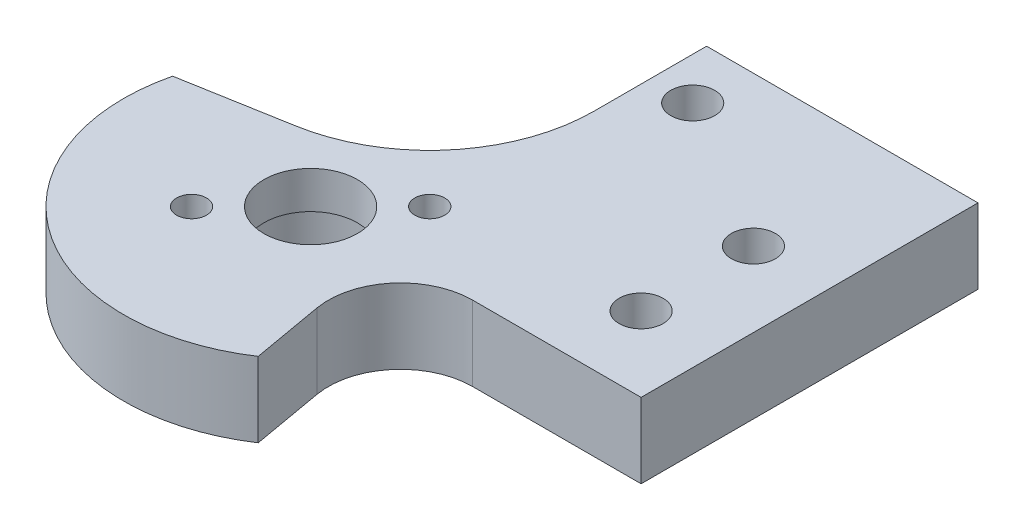
SolidWorks part; units mm, degrees
ref_plane "前视基准面" through (0, 0, 0) normal (0, 0, 1) x (1, 0, 0)
ref_plane "上视基准面" through (0, 0, 0) normal (0, 1, 0) x (1, 0, 0)
ref_plane "右视基准面" through (0, 0, 0) normal (1, 0, 0) x (0, 0, -1)
sketch "草图3" plane through (0, 0, 0) normal (0, 1, 0) x (1, 0, 0)
  line L1 (0, 0) -> (14.5, 0)
  line L2 (0, 0) -> (0, -18)
  line L4 (14.5, 0) -> (14.5, -6)
  line L6 (12.7972, -22.5253) -> (12.1261, -26.3313)
  line L11 (21.7695, -14.6635) -> (27.3774, -15.6523)
  line L12 (17.6569, -18) -> (43.4451, -18) construction
  line L15 (0, -18) -> (9, -18)
  circle A3 centre (4, -14) radius 1.175
  circle A4 centre (4, -8) radius 1.175
  circle A5 centre (12.2426, -3) radius 1.175
  circle A7 centre (17.6569, -18) radius 2.5
  arc A8 (12.1261, -26.3313) -> (27.3774, -15.6523) centre (17.6569, -18) ccw
  circle A9 centre (17.6569, -18) radius 4 construction
  arc A11 (21.7695, -14.6635) -> (14.5, -6) centre (23.2971, -6) cw
  arc A12 (9, -18) -> (12.7972, -22.5253) centre (9, -21.8558) cw
  dimension "D2" = 4
  dimension "D3" = 20
  dimension "D4" = 8
  dimension "D8" = 3
  dimension "D10" = 8
  dimension "D11" = 6
  dimension "D16" = 2.35
  dimension "D17" = 5
  dimension "D1" = 14.5
  dimension "D5" = 100
  dimension "D6" = 90
  dimension "D7" = 18
  dimension "D9" = 2.2574
  dimension "D12" = 6
  dimension "D13" = 17.6569
  dimension "D14" = 18
  dimension "D15" = 9
extrude "凸台-拉伸2" add sketch "草图3" along normal blind 4
hole_wizard "Ø1.6 (1.6) 直径孔1" positions "草图4" profile "草图5" hole size "Ø1.6" standard "GB" end condition through all
sketch "草图4" plane through (0, 4, 0) normal (0, 1, 0) x (1, 0, 0)
  line L0 (17.6569, -18) -> (25.5238, -25.8669) construction
  line L2 (17.6569, -18) -> (29.6181, -18) construction
  line L4 (17.6569, -18) -> (23.9538, -11.703) construction
  point P0 (20.8388, -21.182)
  point P22 (14.4749, -14.818)
  dimension "D1" = 45
  dimension "D2" = 9
sketch "草图5" plane through (20.8388, 4, 21.182) normal (1, 0, 0) x (0, 0, 1)
  line L0 (0, 0) -> (0, 4)
  line L1 (0, 4) -> (0.8, 4)
  line L2 (0.8, 4) -> (0.8, 0)
  line L5 (0.8, 0) -> (0, 0)
  line L11 (0, -6.35) -> (0, 107.95) construction
  dimension "通孔孔直径" = 1.6
  dimension "通孔孔深度" = 4
hole_wizard "Ø2.9 (2.9) 直径孔2" [suppressed] positions "草图9" profile "草图10" hole size "Ø2.9" standard "GB"
sketch "草图9" plane through (0, 0, 0) normal (0, 1, 0) x (1, 0, 0)
  point P0 (20.8388, -21.182)
  point P3 (14.4749, -14.818)
sketch "草图10" plane through (20.8388, 0, 21.182) normal (1, 0, 0) x (0, 0, -1)
  line L0 (0, 0) -> (0, 1.1)
  line L1 (0, 1.1) -> (1.5, 1.1)
  line L2 (1.5, 1.1) -> (1.5, 0)
  line L5 (1.5, 0) -> (0, 0)
  line L10 (0, 1.1) -> (-1.5, 1.1) construction
  line L11 (0, -6.35) -> (0, 107.95) construction
  dimension "孔直径" = 3
  dimension "孔深度" = 1.1
  dimension "导头角度" = 180
mirror "镜向1" about plane through (0, 4, 0) normal (1, 0, 0) of bodies 108 110
delete or keep bodies "实体-删除/保留 3" type delete bodies bodies 108
sketch "草图11" plane through (0, 0, 0) normal (0, -1, 0) x (-1, 0, 0)
  circle A0 centre (14.4749, -14.818) radius 1.6
  circle A1 centre (20.8388, -21.182) radius 1.6
  dimension "D1" = 3.2
  dimension "D2" = 3.2
extrude "切除-拉伸1" cut sketch "草图11" against normal blind 1
sketch "草图12" plane through (0, 0, 0) normal (0, -1, 0) x (-1, 0, 0)
  circle A0 centre (17.6569, -18) radius 3.05
  dimension "D1" = 6.1
extrude "切除-拉伸2" cut sketch "草图12" against normal blind 2
sketch "草图13" plane through (0, 1, 0) normal (0, -1, 0) x (-1, 0, 0)
  circle A0 centre (14.4749, -14.818) radius 0.765
  circle A1 centre (20.8388, -21.182) radius 0.765
  dimension "D1" = 1.53
  dimension "D2" = 1.53
